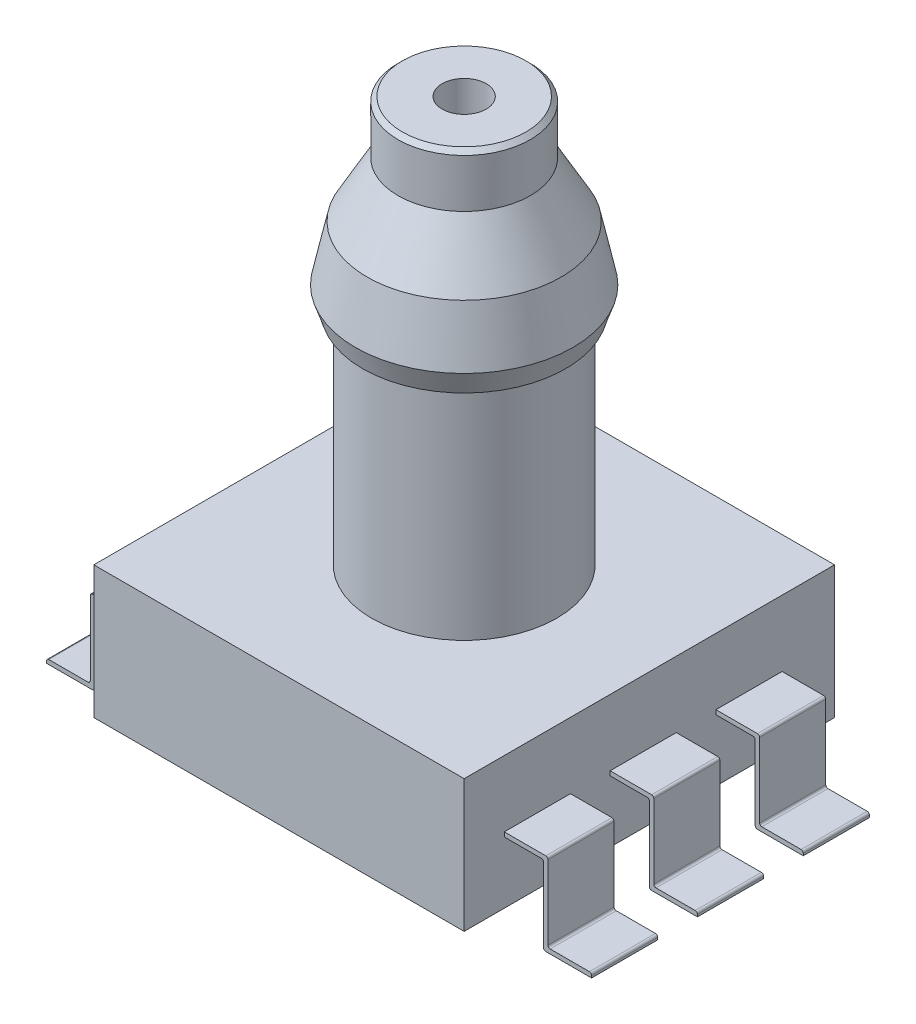
SolidWorks part; units mm, degrees
ref_plane "Front Plane" through (0, 0, 0) normal (0, 0, 1) x (1, 0, 0)
ref_plane "Top Plane" through (0, 0, 0) normal (0, 1, 0) x (1, 0, 0)
ref_plane "Right Plane" through (0, 0, 0) normal (1, 0, 0) x (0, 0, -1)
sketch "Sketch1" plane through (0, 0, 0) normal (0, 1, 0) x (1, 0, 0)
  line L1 (-4.2, 4.2) -> (4.2, 4.2)
  line L2 (-4.2, 4.2) -> (-4.2, -4.2)
  line L3 (-4.2, -4.2) -> (4.2, -4.2)
  line L4 (4.2, 4.2) -> (4.2, -4.2)
  line L5 (-4.2, 4.2) -> (4.2, -4.2) construction
  line L6 (-4.2, -4.2) -> (4.2, 4.2) construction
  point P0 (0, 0)
  dimension "D1" = 8.4
extrude "Boss-Extrude1" add sketch "Sketch1" along normal blind 3
ref_plane "Plane1" through (0, 0, 3.29) normal (0, 0, 1) x (1, 0, 0)
sketch "Sketch2" plane through (0, 0, 3.29) normal (0, 0, 1) x (1, 0, 0)
  line L0 (4.2, 1.5) -> (6.18, 1.5) construction
  line L1 (4.2, 3) -> (4.2, 0) construction
  line L2 (6.18, 1.5) -> (6.18, -0.38) construction
  line L3 (4.2, 1.5) -> (5.14, 1.5)
  line L4 (5.19, 1.45) -> (5.19, -0.23)
  line L5 (5.24, -0.28) -> (6.13, -0.28)
  line L6 (4.2, 1.5) -> (4.2, 1.4)
  line L7 (4.2, 1.4) -> (5.04, 1.4)
  line L8 (5.09, 1.35) -> (5.09, -0.33)
  line L9 (5.14, -0.38) -> (6.18, -0.38)
  line L10 (6.18, -0.38) -> (6.18, -0.33)
  arc A0 (6.13, -0.28) -> (6.18, -0.33) centre (6.13, -0.33) cw
  arc A1 (5.09, -0.33) -> (5.14, -0.38) centre (5.14, -0.33) ccw
  arc A2 (5.04, 1.4) -> (5.09, 1.35) centre (5.04, 1.35) cw
  arc A3 (5.14, 1.5) -> (5.19, 1.45) centre (5.14, 1.45) cw
  arc A4 (5.19, -0.23) -> (5.24, -0.28) centre (5.24, -0.23) ccw
  point P15 (6.18, -0.28)
  point P22 (5.19, 1.5)
  dimension "D7" = 0.05
  dimension "D1" = 1.98
  dimension "D2" = 1.5
  dimension "D3" = 0.38
  dimension "D4" = 0.1
  dimension "D5" = 0.1
  dimension "D6" = 0.1
extrude "Boss-Extrude2" add sketch "Sketch2" against normal blind 1.5 separate body
pattern_linear "LPattern1" count 3 spacing 2.4 along (0, 0, -1) of "Boss-Extrude2"
mirror "Mirror1" about plane through (0, 0, 0) normal (1, 0, 0) of "LPattern1", "Boss-Extrude2"
sketch "Sketch3" plane through (0, 3, 0) normal (0, 1, 0) x (1, 0, 0)
  circle A0 centre (0, 0) radius 2.1
  dimension "D1" = 4.2
extrude "Boss-Extrude3" add sketch "Sketch3" along normal blind 5
sketch "Sketch4" plane through (0, 0, 0) normal (0, 0, 1) x (1, 0, 0)
  line L0 (0, 8) -> (0, 11) construction
  line L1 (2.1, 8) -> (-2.1, 8) construction
  line L2 (0, 8) -> (-2.3, 8)
  line L3 (0, 8.5) -> (-2.465, 8.5) construction
  line L4 (-2.3, 8) -> (-2.465, 8.5)
  line L5 (0, 8.5) -> (0, 11) construction
  line L6 (0, 11) -> (-1.5, 11)
  line L7 (0, 9.75) -> (-2.2, 9.75) construction
  line L8 (-2.465, 8.5) -> (-2.2, 9.75)
  line L9 (-2.2, 9.75) -> (-1.5, 11)
  line L10 (0, 8) -> (0, 11)
  dimension "D1" = 3
  dimension "D2" = 2.3
  dimension "D3" = 0.5
  dimension "D4" = 2.465
  dimension "D5" = 1.5
  dimension "D6" = 2.2
revolve "Revolve1" add sketch "Sketch4" angle 360 about L10
sketch "Sketch5" plane through (0, 11, 0) normal (0, 1, 0) x (1, 0, 0)
  circle A1 centre (0, 0) radius 1.5
  circle A2 centre (0, 0) radius 1.5
  dimension "D1" = 0
extrude "Boss-Extrude4" add sketch "Sketch5" along normal blind 1.2 contours A2
chamfer "Chamfer1" distance 0.1 angle 45 1 edges at (0, 12.2, 1.5)
sketch "Sketch7" plane through (0, 12.2, 0) normal (0, 1, 0) x (1, 0, 0)
  circle A0 centre (0, 0) radius 0.5
  dimension "D1" = 1
extrude "Cut-Extrude1" cut sketch "Sketch7" against normal up to surface (9.2 mm away) up to face at (0, 3, 2.1)
